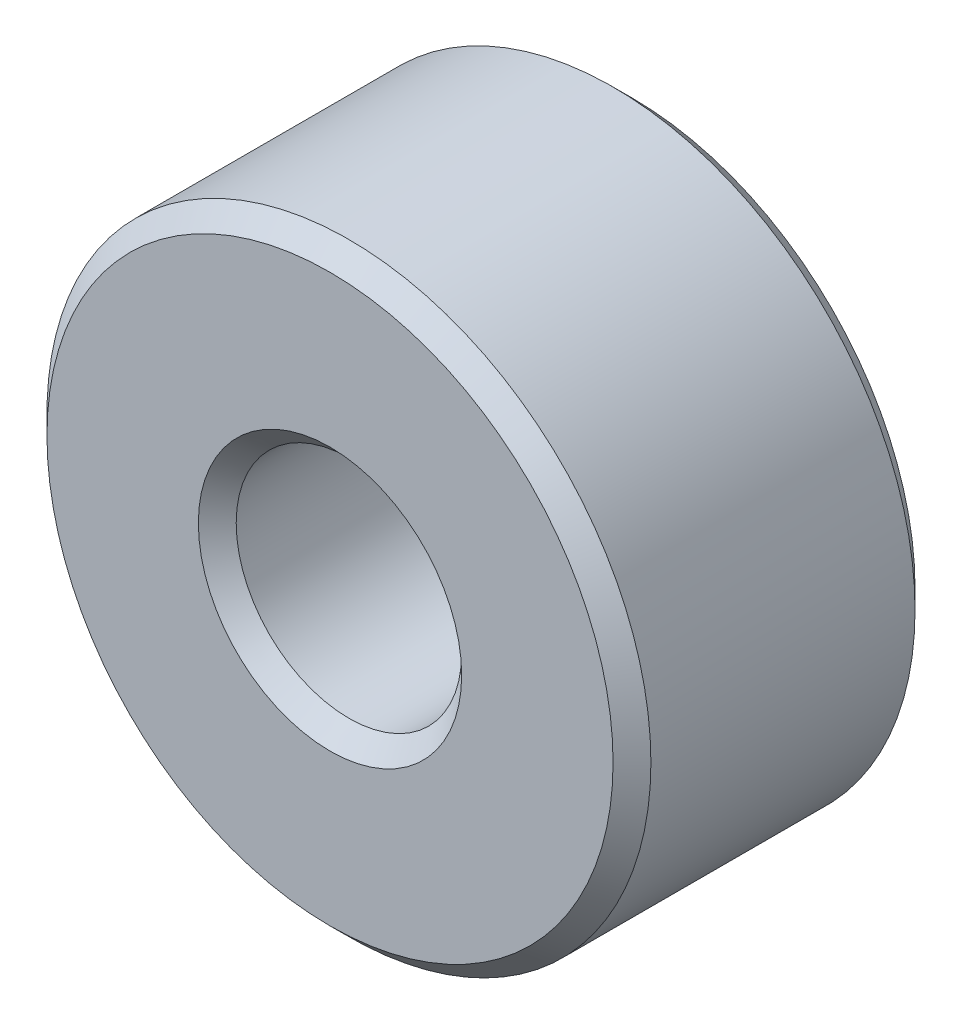
SolidWorks part; units mm, degrees
ref_plane "Front Plane" through (0, 0, 0) normal (0, 0, 1) x (1, 0, 0)
ref_plane "Top Plane" through (0, 0, 0) normal (0, 1, 0) x (1, 0, 0)
ref_plane "Right Plane" through (0, 0, 0) normal (1, 0, 0) x (0, 0, -1)
sketch "Sketch1" plane through (0, 0, 0) normal (0, 0, 1) x (1, 0, 0)
  circle A0 centre (0, 0) radius 4.7625 construction
  circle A1 centre (0, 0) radius 1.778 construction
  point P4 (0, 4.7625)
  dimension "ID" = 3.556
  dimension "OD" = 9.525
sketch "Sketch2" plane through (0, 0, 0) normal (1, 0, 0) x (0, 0, -1)
  line L0 (-2.3813, 4.7625) -> (2.3813, 4.7625) construction
  dimension "Length" = 4.7625
sketch "Sketch3" plane through (0, 0, 0) normal (0, 0, 1) x (1, 0, 0)
  circle A0 centre (0, 0) radius 1.778 construction
  circle A1 centre (0, 0) radius 4.7625 construction
  circle A2 centre (0, 0) radius 1.778
  circle A3 centre (0, 0) radius 4.7625
extrude "Boss-Extrude1" add sketch "Sketch3" against normal up to vertex (2.3813 mm away) and the other way up to vertex (2.3813 mm away) up to point (0, 4.7625, -2.3813) other way up to point (0, 4.7625, 2.3813)
chamfer "Chamfer1" distance 0.2984 angle 45 4 edges at (4.7625, 0, 2.3813) (4.7625, 0, -2.3813) (1.778, 0, 2.3813) (1.778, 0, -2.3813)
equation "\"D1@Chamfer1\"=(\"OD@Sketch1\"-\"ID@Sketch1\")*0.05"
